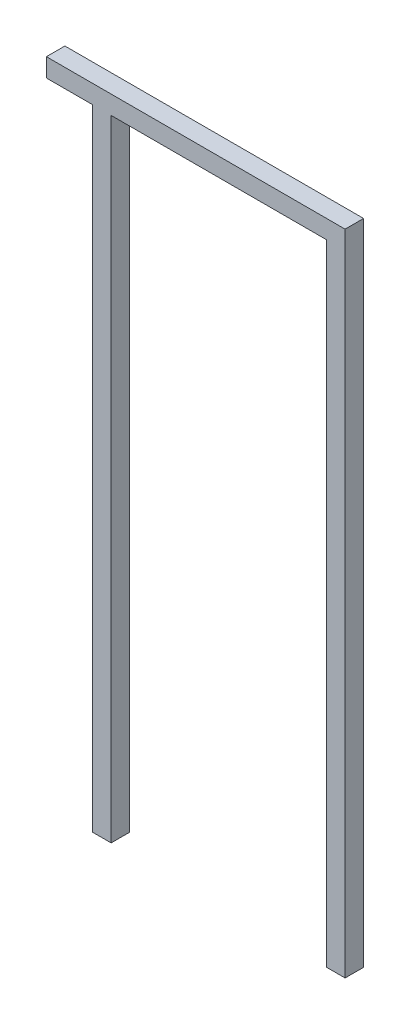
SolidWorks part; units mm, degrees
ref_plane "Front Plane" through (0, 0, 0) normal (0, 0, 1) x (1, 0, 0)
ref_plane "Top Plane" through (0, 0, 0) normal (0, 1, 0) x (1, 0, 0)
ref_plane "Right Plane" through (0, 0, 0) normal (1, 0, 0) x (0, 0, -1)
sketch "Sketch1" plane through (0, 0, 0) normal (0, 0, 1) x (1, 0, 0)
  line L0 (-279.6626, 140.9939) -> (43.3374, 140.9939)
  line L1 (43.3374, 140.9939) -> (43.3374, -560.3361)
  line L2 (43.3374, -560.3361) -> (23.3374, -560.3361)
  line L3 (23.3374, -560.3361) -> (23.3374, 120.9939)
  line L4 (23.3374, 120.9939) -> (-209.6626, 120.9939)
  line L5 (-209.6626, 120.9939) -> (-209.6626, -560.3361)
  line L6 (-209.6626, -560.3361) -> (-229.6626, -560.3361)
  line L7 (-229.6626, -560.3361) -> (-229.6626, 120.9939)
  line L8 (-229.6626, 120.9939) -> (-279.6626, 120.9939)
  line L9 (-279.6626, 140.9939) -> (-279.6626, 120.9939)
  dimension "D1" = 701.33
  dimension "D2" = 50
  dimension "D3" = 323
  dimension "D4" = 20
  dimension "D5" = 20
  dimension "D6" = 20
  dimension "D7" = 20
  dimension "D8" = 701.33
extrude "Boss-Extrude1" add sketch "Sketch1" along normal blind 20
